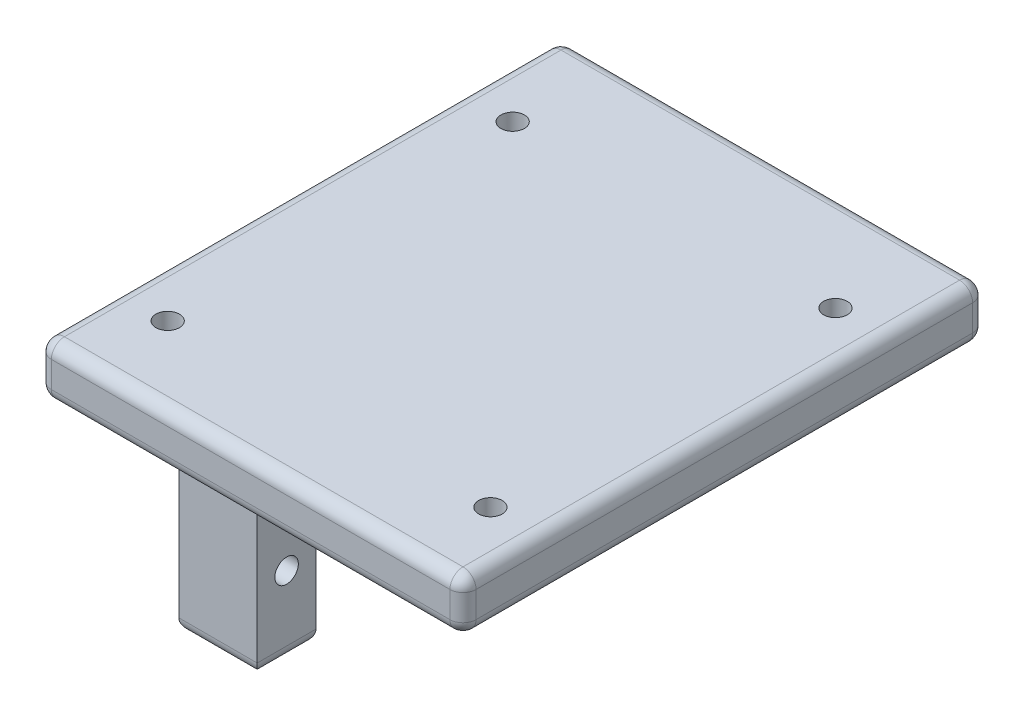
SolidWorks part; units mm, degrees
ref_plane "Front Plane" through (0, 0, 0) normal (0, 0, 1) x (1, 0, 0)
ref_plane "Top Plane" through (0, 0, 0) normal (0, 1, 0) x (1, 0, 0)
ref_plane "Right Plane" through (0, 0, 0) normal (1, 0, 0) x (0, 0, -1)
sketch "Sketch1" plane through (0, 0, 0) normal (0, 1, 0) x (1, 0, 0)
  line L1 (-16.25, 40) -> (16.25, 40)
  line L2 (-16.25, 40) -> (-16.25, 0)
  line L3 (-16.25, 0) -> (16.25, 0)
  line L4 (16.25, 40) -> (16.25, 0)
  point P4 (0, 0)
  dimension "D1" = 32.5
  dimension "D2" = 40
extrude "Base" add sketch "Sketch1" along normal blind 4
sketch "Sketch4" plane through (0, 0, 0) normal (0, -1, 0) x (1, 0, 0)
  line L0 (-12.35, 0) -> (-12.35, -40) construction
  line L1 (-16.25, 0) -> (16.25, 0) construction
  line L2 (16.25, -40) -> (-16.25, -40) construction
  line L3 (-16.25, -40) -> (-16.25, 0) construction
  line L4 (0, 0) -> (0, -40) construction
  circle A0 centre (-12.35, -6) radius 0.9
  circle A1 centre (-12.35, -32.4) radius 0.9
  circle A2 centre (12.35, -32.4) radius 0.9
  circle A3 centre (12.35, -6) radius 0.9
  dimension "D2" = 26.4
  dimension "D3" = 6
  dimension "D4" = 1.8
  dimension "D1" = 3.9
extrude "Scanner Mounting Holes" cut sketch "Sketch4" against normal through all
sketch "Sketch6" plane through (0, 0, 0) normal (0, -1, 0) x (1, 0, 0)
  line L0 (-16.25, -40) -> (-16.25, 0) construction
  line L1 (-9.25, -3.75) -> (-3.25, -3.75)
  line L2 (-9.25, -3.75) -> (-9.25, -8.25)
  line L3 (-9.25, -8.25) -> (-3.25, -8.25)
  line L4 (-3.25, -3.75) -> (-3.25, -8.25)
  line L5 (-11.45, -6) -> (-13.25, -6) construction
  line L7 (-9.25, -36.05) -> (-3.25, -36.05)
  line L8 (-9.25, -36.05) -> (-9.25, -31.55)
  line L9 (-9.25, -31.55) -> (-3.25, -31.55)
  line L10 (-3.25, -36.05) -> (-3.25, -31.55)
  circle A0 centre (-12.35, -6) radius 0.9 construction
  point P11 (-9.25, -6)
  point P16 (-9.25, -33.8)
  dimension "D1" = 7
  dimension "D2" = 6
  dimension "D3" = 4.5
  dimension "D4" = 27.8
  dimension "D5" = 4.5
extrude "Servo Mounting Platform" add sketch "Sketch6" along normal blind 14
sketch "Sketch7" plane through (-9.25, 0, 0) normal (-1, 0, 0) x (0, 0, 1)
  line L0 (-33.8, 0) -> (-33.8, -14) construction
  line L1 (-31.55, 0) -> (-36.05, 0) construction
  line L2 (-31.55, -14) -> (-36.05, -14) construction
  line L3 (-6, 0) -> (-6, -14) construction
  line L4 (-3.75, 0) -> (-8.25, 0) construction
  line L5 (-3.75, -14) -> (-8.25, -14) construction
  line L6 (-33.8, -8) -> (-6, -8) construction
  circle A0 centre (-33.8, -8) radius 0.9
  circle A1 centre (-6, -8) radius 0.9
  dimension "D1" = 6
  dimension "D2" = 1.8
extrude "Servo Mounting Holes" cut sketch "Sketch7" against normal up to next
fillet "Fillet1" radius 1 24 edges at (0, 4, 0) (0, 0, 0) (16.25, 2, 0) (16.25, 4, -20) (16.25, 0, -20) (16.25, 2, -40) (0, 4, -40) (0, 0, -40) (-16.25, 2, -40) (-16.25, 4, -20) (-16.25, 2, 0) (-16.25, 0, -20) (-6.25, -14, -31.55) (-3.25, -14, -33.8) (-6.25, -14, -36.05) (-9.25, -14, -33.8) (-6.25, -14, -3.75) (-3.25, -14, -6) (-6.25, -14, -8.25) (-9.25, -14, -6) (-6.25, 0, -36.05) (-6.25, 0, -31.55) (-6.25, 0, -8.25) (-6.25, 0, -3.75)
